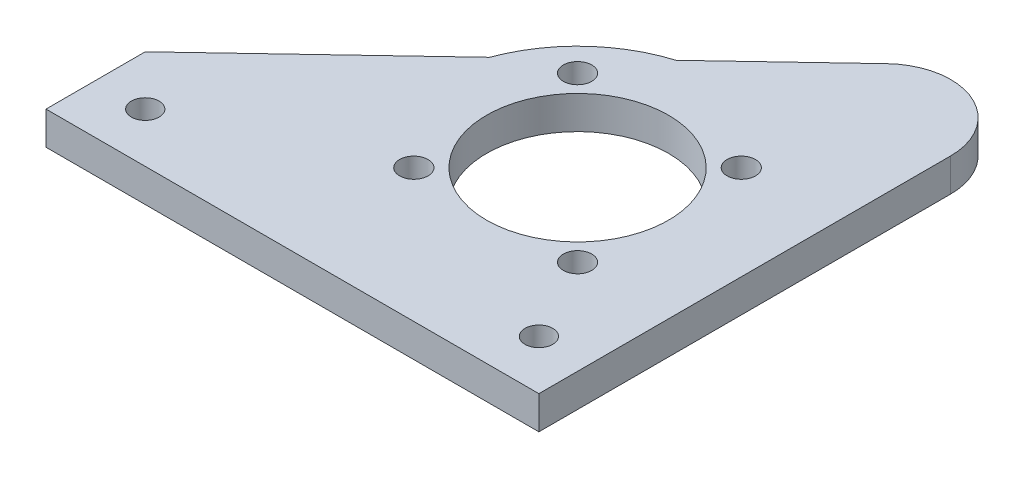
SolidWorks part; units mm, degrees
material "5052-H34"
ref_plane "正面" through (0, 0, 0) normal (0, 0, 1) x (1, 0, 0)
ref_plane "平面" through (0, 0, 0) normal (0, 1, 0) x (1, 0, 0)
ref_plane "右側面" through (0, 0, 0) normal (1, 0, 0) x (0, 0, -1)
sketch "ｽｹｯﾁ1" plane through (0, 0, 0) normal (0, 1, 0) x (1, 0, 0)
  line L0 (0, 0) -> (-130.5, 0) construction
  line L1 (-130.5, 0) -> (-130.5, 65) construction
  line L2 (0, 0) -> (0, 90) construction
  line L3 (-130.5, 65) -> (-49.6542, 25) construction
  line L4 (5, 0) -> (5, 90)
  line L5 (-62.0286, 12.6256) -> (-37.2799, 12.6256) construction
  line L6 (-62.0286, 12.6256) -> (-62.0286, 37.3744) construction
  line L7 (-62.0286, 37.3744) -> (-37.2799, 37.3744) construction
  line L8 (-37.2799, 12.6256) -> (-37.2799, 37.3744) construction
  line L9 (-62.0286, 12.6256) -> (-37.2799, 37.3744) construction
  line L10 (-62.0286, 37.3744) -> (-37.2799, 12.6256) construction
  line L11 (0, -7.5) -> (-130.5, -7.5)
  line L12 (0, -7.5) -> (5, -7.5)
  line L13 (5, -7.5) -> (5, 0)
  line L14 (5, 90) -> (5, 95)
  line L15 (5, 95) -> (-5, 95)
  line L16 (-5, 95) -> (-56.2637, 46.5073)
  line L17 (-97.5, 7.5) -> (-97.5, -7.5)
  line L18 (-56.2637, 46.5073) -> (-68.9221, 34.5332) construction
  line L19 (-70.7615, 32.7932) -> (-97.5, 7.5)
  line L20 (-68.9221, 34.5332) -> (-70.7615, 32.7932) construction
  circle A0 centre (0, 0) radius 2.1
  circle A1 centre (-49.6542, 25) radius 13.75
  circle A2 centre (-37.2799, 37.3744) radius 2.15
  circle A3 centre (-37.2799, 12.6256) radius 2.15
  circle A4 centre (-62.0286, 12.6256) radius 2.15
  circle A5 centre (-62.0286, 37.3744) radius 2.15
  circle A6 centre (0, 90) radius 2.15
  circle A7 centre (-90, 0) radius 2.1
  arc A8 (-56.2637, 46.5073) -> (-70.7615, 32.7932) centre (-49.6542, 25) ccw
  arc A9 (-70.7615, 32.7932) -> (-56.2637, 46.5073) centre (-49.6542, 25) ccw construction
  circle A10 centre (-30.5, 0) radius 2.1
  point P21 (-49.6542, 25)
  dimension "D3" = 4.2
  dimension "D4" = 27.5
  dimension "D7" = 4.3
  dimension "D9" = 4.3
  dimension "D13" = 45
  dimension "D1" = 130.5
  dimension "D2" = 65
  dimension "D5" = 90.2
  dimension "D6" = 35
  dimension "D10" = 90
  dimension "D11" = 90
  dimension "D12" = 25
  dimension "D16" = 15
  dimension "D17" = 10
  dimension "D18" = 5
  dimension "D19" = 7.5
  dimension "D20" = 67
  dimension "D14" = 5
  dimension "D15" = 7.5
  dimension "D8" = 4
extrude "ﾎﾞｽ - 押し出し1" add sketch "ｽｹｯﾁ1" along normal blind 5 contours L16 A8 L19 L17 L11 L12 L13 L4 L14 L15 A0 A1 A2 A3 A4 A5 A6 A7
sketch "ｽｹｯﾁ2" plane through (0, 5, 0) normal (0, 1, 0) x (1, 0, 0)
  line L0 (-23, -7.5) -> (-23, 77.973)
  line L1 (5, -7.5) -> (-97.5, -7.5) construction
  line L2 (-5, 95) -> (-56.2637, 46.5073) construction
  line L3 (-23, 77.973) -> (-5, 95)
  line L4 (5, 95) -> (-5, 95) construction
  line L5 (-5, 95) -> (5, 95)
  line L6 (5, 95) -> (5, -7.5)
  line L7 (5, -7.5) -> (-23, -7.5)
  circle A0 centre (-30.5, 0) radius 2.1 construction
  dimension "D1" = 7.5
extrude "ｶｯﾄ - 押し出し1" cut sketch "ｽｹｯﾁ2" against normal up to surface (5 mm away) up to face at (-30.5, 0, 2.1)
fillet "ﾌｨﾚｯﾄ1" radius 10 1 edges at (-23, 2.5, -77.973)
equation "\"D5@ｽｹｯﾁ1\"=70+20+0.2"
